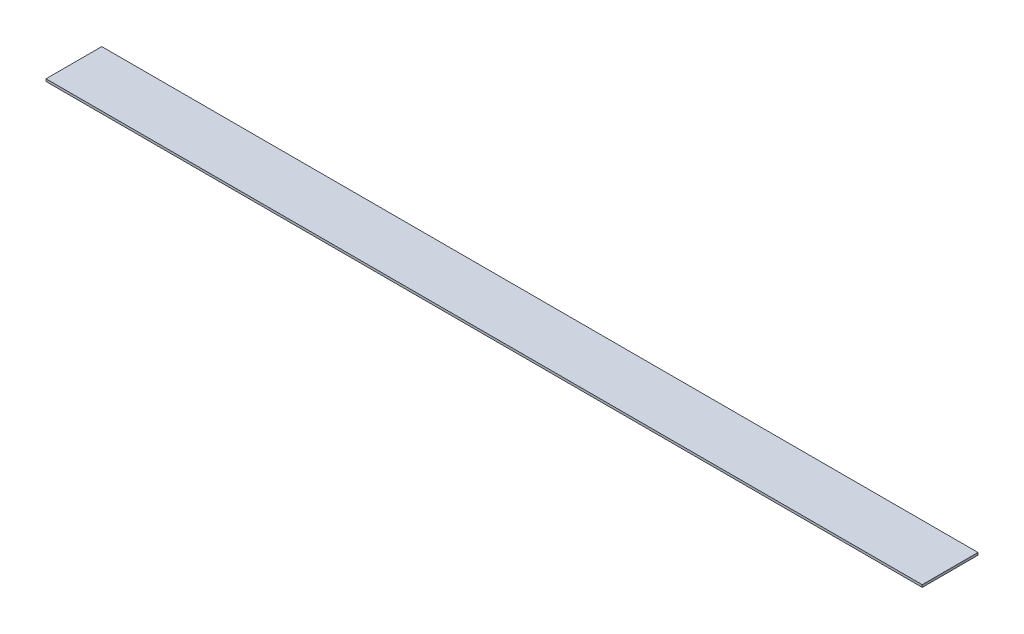
SolidWorks part; units mm, degrees
ref_plane "Alzado" through (0, 0, 0) normal (0, 0, 1) x (1, 0, 0)
ref_plane "Planta" through (0, 0, 0) normal (0, 1, 0) x (1, 0, 0)
ref_plane "Vista lateral" through (0, 0, 0) normal (1, 0, 0) x (0, 0, -1)
sketch "Croquis1" plane through (0, 0, 0) normal (0, 1, 0) x (1, 0, 0)
  line L1 (550, -35) -> (-550, -35)
  line L2 (550, -35) -> (550, 35)
  line L3 (550, 35) -> (-550, 35)
  line L4 (-550, -35) -> (-550, 35)
  line L5 (550, -35) -> (-550, 35) construction
  line L6 (550, 35) -> (-550, -35) construction
  point P0 (0, 0)
  dimension "D1" = 1100
  dimension "D2" = 70
extrude "Extruir1" add sketch "Croquis1" along normal blind 3
sketch "Croquis2" plane through (0, 3, 0) normal (0, 1, 0) x (1, 0, 0)
  line L0 (0, 35) -> (0, -35) construction
  line L1 (-550, 35) -> (-510, 35)
  line L2 (-550, 35) -> (-550, -5)
  line L3 (-550, -5) -> (-510, -5)
  line L4 (-510, 35) -> (-510, -5)
  line L5 (550, 35) -> (-550, 35) construction
  line L6 (-550, -35) -> (550, -35) construction
  line L7 (510, 35) -> (510, -5)
  line L8 (550, -5) -> (510, -5)
  line L9 (550, 35) -> (550, -5)
  line L10 (550, 35) -> (510, 35)
  dimension "D1" = 40
  dimension "D2" = 40
extrude "Extruir2" [suppressed] cut sketch "Croquis2" against normal blind 10
